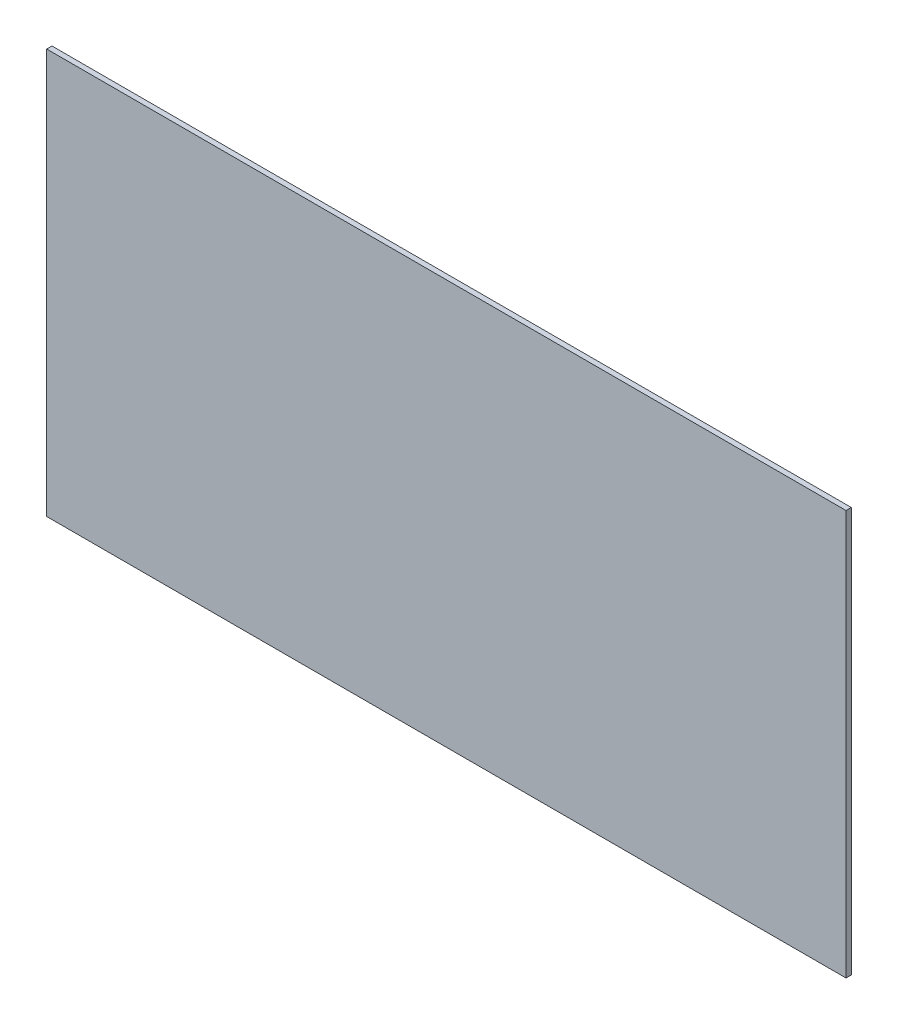
SolidWorks part; units mm, degrees
ref_plane "Спереди" through (0, 0, 0) normal (0, 0, 1) x (1, 0, 0)
ref_plane "Сверху" through (0, 0, 0) normal (0, 1, 0) x (1, 0, 0)
ref_plane "Справа" through (0, 0, 0) normal (1, 0, 0) x (0, 0, -1)
sketch "Эскиз1" plane through (0, 0, 0) normal (0, 0, 1) x (1, 0, 0)
  line L1 (0, 0) -> (1520, 0)
  line L2 (0, 0) -> (0, 770)
  line L3 (0, 770) -> (1520, 770)
  line L4 (1520, 0) -> (1520, 770)
  dimension "D1" = 1520
  dimension "D2" = 770
extrude "Бобышка-Вытянуть1" add sketch "Эскиз1" along normal blind 10
